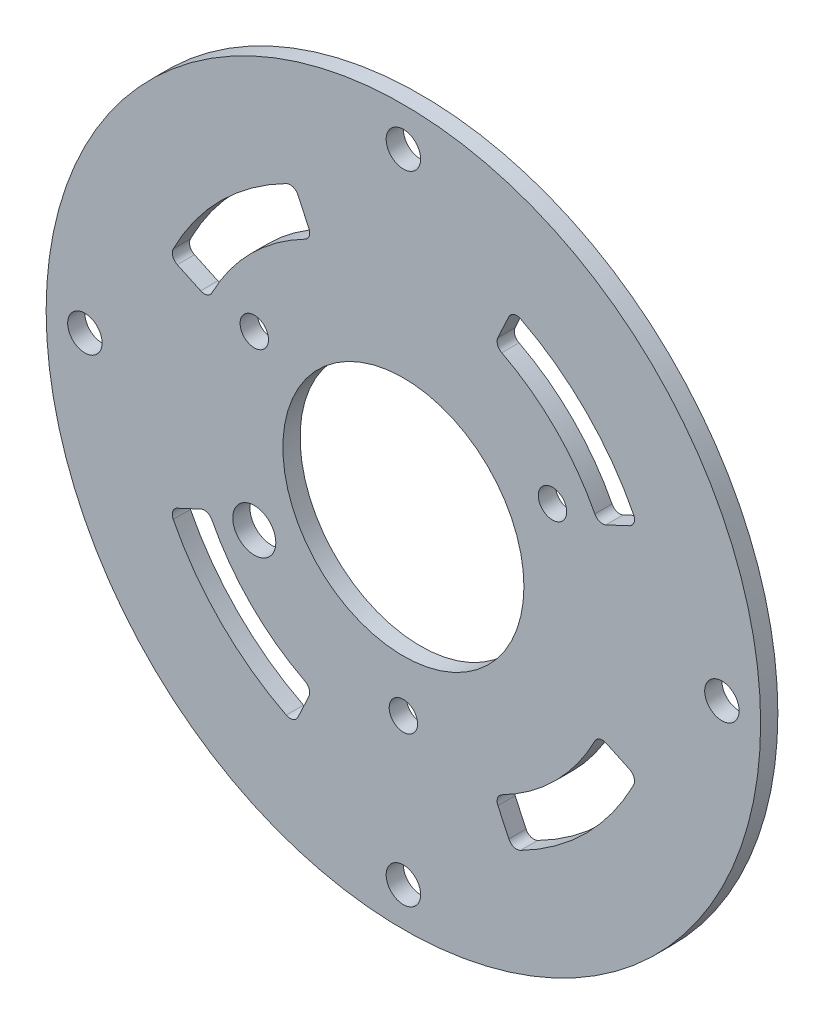
SolidWorks part; units mm, degrees
material "Thornel Mat VMA"
ref_plane "前视基准面" through (0, 0, 0) normal (0, 0, 1) x (1, 0, 0)
ref_plane "上视基准面" through (0, 0, 0) normal (0, 1, 0) x (1, 0, 0)
ref_plane "右视基准面" through (0, 0, 0) normal (1, 0, 0) x (0, 0, -1)
sketch "草图1" plane through (0, 0, 0) normal (0, 0, 1) x (1, 0, 0)
  circle A0 centre (0, -37) radius 2
  circle A2 centre (-37, 0) radius 2
  circle A3 centre (0, 37) radius 2
  circle A4 centre (37, 0) radius 2
  circle A5 centre (0, 0) radius 41.5
  circle A6 centre (0, 0) radius 14
  point P12 (0, 0)
  dimension "D1" = 2
  dimension "D2" = 4
  dimension "D3" = 37
  dimension "D4" = 41.5
  dimension "D5" = 14
extrude "凸台-拉伸1" add sketch "草图1" along normal blind 2
sketch "草图4" plane through (0, 0, 2) normal (0, 0, 1) x (1, 0, 0)
  line L0 (10.5655, 22.6577) -> (12.6785, 27.1892)
  line L1 (22.6577, 10.5655) -> (27.1892, 12.6785)
  line L2 (0, 0) -> (41.5, 0)
  line L3 (10.5655, -22.6577) -> (12.6785, -27.1892)
  line L4 (22.6577, -10.5655) -> (27.1892, -12.6785)
  line L5 (-22.6577, -10.5655) -> (-27.1892, -12.6785)
  line L6 (-10.5655, -22.6577) -> (-12.6785, -27.1892)
  line L7 (-10.5655, 22.6577) -> (-12.6785, 27.1892)
  line L8 (-22.6577, 10.5655) -> (-27.1892, 12.6785)
  arc A0 (22.6577, 10.5655) -> (10.5655, 22.6577) centre (0, 0) ccw
  arc A1 (27.1892, 12.6785) -> (12.6785, 27.1892) centre (0, 0) ccw
  circle A2 centre (0, 0) radius 41.5 construction
  arc A3 (12.6785, -27.1892) -> (27.1892, -12.6785) centre (0, 0) ccw
  arc A4 (10.5655, -22.6577) -> (22.6577, -10.5655) centre (0, 0) ccw
  arc A5 (-27.1892, -12.6785) -> (-12.6785, -27.1892) centre (0, 0) ccw
  arc A6 (-22.6577, -10.5655) -> (-10.5655, -22.6577) centre (0, 0) ccw
  arc A7 (-12.6785, 27.1892) -> (-27.1892, 12.6785) centre (0, 0) ccw
  arc A8 (-10.5655, 22.6577) -> (-22.6577, 10.5655) centre (0, 0) ccw
  point P25 (0, 0)
  dimension "D1" = 25
  dimension "D2" = 30
  dimension "D3" = 4
  dimension "D4" = 25
extrude "切除-拉伸3" cut sketch "草图4" against normal blind 2 contours A8 L7 A7 L8 | L1 A1 L0 A0 | A6 L5 A5 L6 | A4 L3 A3 L4
fillet "圆角1" radius 1 16 edges at (-22.6577, -10.5655, 1) (-27.1892, -12.6785, 1) (-10.5655, -22.6577, 1) (-12.6785, -27.1892, 1) (22.6577, -10.5655, 1) (27.1892, -12.6785, 1) (10.5655, -22.6577, 1) (12.6785, -27.1892, 1) (22.6577, 10.5655, 1) (10.5655, 22.6577, 1) (12.6785, 27.1892, 1) (27.1892, 12.6785, 1) (-10.5655, 22.6577, 1) (-22.6577, 10.5655, 1) (-27.1892, 12.6785, 1) (-12.6785, 27.1892, 1)
sketch "草图5" plane through (0, 0, 2) normal (0, 0, 1) x (1, 0, 0)
  line L1 (-17.3205, 10) -> (0, -20) construction
  line L2 (0, -20) -> (17.3205, 10) construction
  line L3 (17.3205, 10) -> (-17.3205, 10) construction
  circle A0 centre (0, 0) radius 10 construction
  circle A1 centre (-17.3205, 10) radius 1.65
  circle A2 centre (17.3205, 10) radius 1.65
  circle A3 centre (0, -20) radius 1.65
  dimension "D2" = 3.3
  dimension "D3" = 3.3
  dimension "D4" = 3.3
  dimension "D1" = 20
extrude "切除-拉伸4" cut sketch "草图5" against normal blind 10
sketch "草图6" plane through (0, 0, 2) normal (0, 0, 1) x (1, 0, 0)
  line L0 (-17.3205, -10) -> (0, 0) construction
  line L1 (0, 0) -> (0, -20) construction
  circle A0 centre (-17.3205, -10) radius 2.5
  dimension "D1" = 5
  dimension "D2" = 20
  dimension "D3" = 60
extrude "切除-拉伸5" cut sketch "草图6" against normal blind 10
